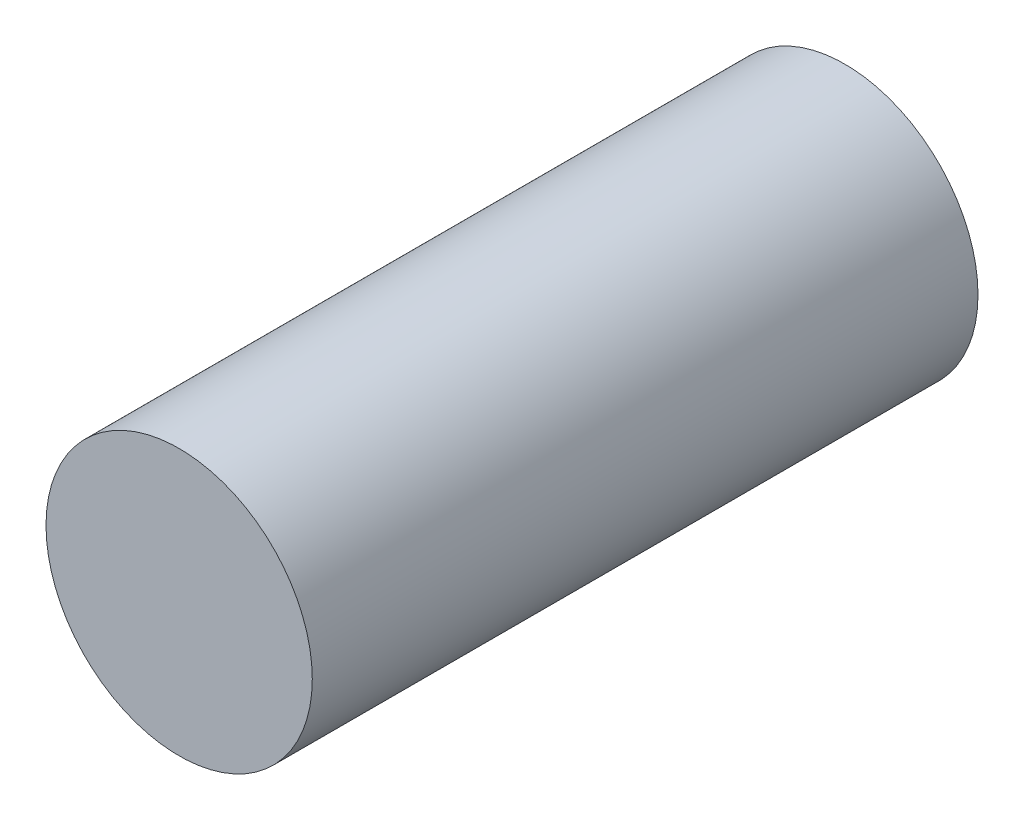
SolidWorks part; units mm, degrees
ref_plane "Front Plane" through (0, 0, 0) normal (0, 0, 1) x (1, 0, 0)
ref_plane "Top Plane" through (0, 0, 0) normal (0, 1, 0) x (1, 0, 0)
ref_plane "Right Plane" through (0, 0, 0) normal (1, 0, 0) x (0, 0, -1)
sketch "Sketch1" plane through (0, 0, 0) normal (0, 0, 1) x (1, 0, 0)
  circle A0 centre (0, 0) radius 254
  dimension "D1" = 508
extrude "Boss-Extrude1" add sketch "Sketch1" along normal blind 1270
